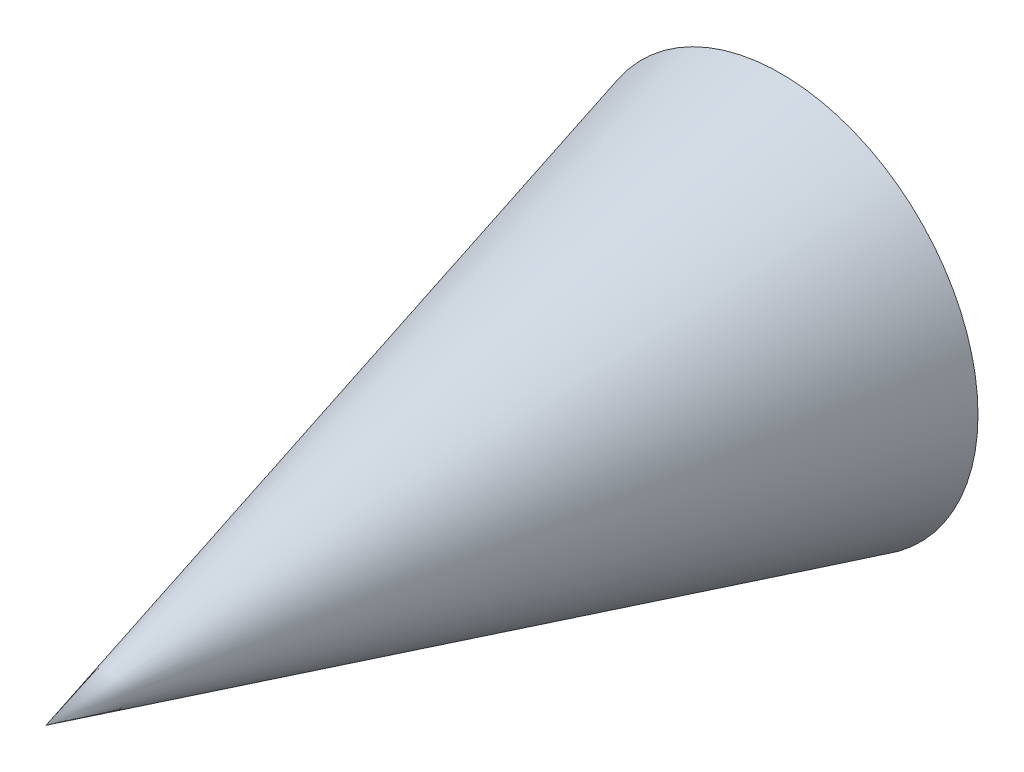
SolidWorks part; units mm, degrees
ref_plane "前基準面" through (0, 0, 0) normal (0, 0, 1) x (1, 0, 0)
ref_plane "上基準面" through (0, 0, 0) normal (0, 1, 0) x (1, 0, 0)
ref_plane "右基準面" through (0, 0, 0) normal (1, 0, 0) x (0, 0, -1)
sketch "草圖1" plane through (0, 0, 0) normal (1, 0, 0) x (0, 0, -1)
  line L0 (0, 0) -> (27.9904, 7.5)
  line L1 (0, 0) -> (3.8637, 0)
  line L2 (0, 0) -> (75.9875, 0) construction
  line L3 (3.8637, 0) -> (27.9904, 6.4647)
  line L4 (27.9904, 7.5) -> (27.9904, 6.4647)
  dimension "D1" = 15
  dimension "D3" = 7.5
  dimension "D5" = 1
revolve "旋轉1" add sketch "草圖1" angle 360 about L2
sketch "草圖4" plane through (0, 0, -27.9904) normal (0, 0, -1) x (-1, 0, 0)
  line L0 (0, 7.5) -> (0, -7.5) construction
  line L1 (-7.5, 0) -> (7.5, 0) construction
  circle A0 centre (0, 0) radius 7.5 construction
ref_plane "平面2" through (0, 0, 0) normal (0, 1, 0) x (1, 0, 0)
